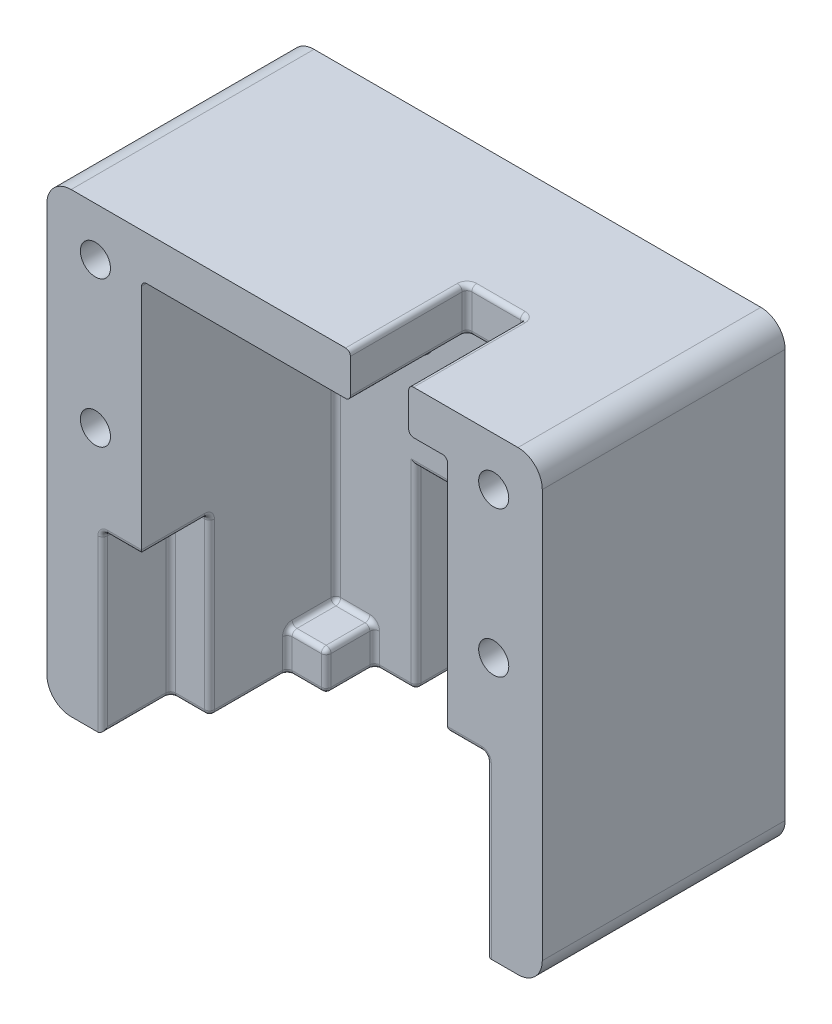
SolidWorks part; units mm, degrees
ref_plane "Front Plane" through (0, 0, 0) normal (0, 0, 1) x (1, 0, 0)
ref_plane "Top Plane" through (0, 0, 0) normal (0, 1, 0) x (1, 0, 0)
ref_plane "Right Plane" through (0, 0, 0) normal (1, 0, 0) x (0, 0, -1)
sketch "Sketch1" plane through (0, 0, 0) normal (0, 0, 1) x (1, 0, 0)
  line L0 (0, 0) -> (51, 0)
  line L1 (51, 0) -> (51, 47)
  line L2 (51, 47) -> (0, 47)
  line L3 (0, 47) -> (0, 0)
  dimension "D1" = 51
  dimension "D2" = 47
extrude "Boss-Extrude1" add sketch "Sketch1" along normal blind 5
sketch "Sketch2" plane through (0, 0, 5) normal (0, 0, 1) x (1, 0, 0)
  line L0 (0, 0) -> (0, 47)
  line L1 (0, 47) -> (51, 47)
  line L2 (51, 47) -> (51, 0)
  line L3 (51, 0) -> (41.25, 0)
  line L4 (0, 0) -> (51, 0) construction
  line L5 (41.25, 0) -> (41.25, 42.5)
  line L6 (41.25, 42.5) -> (9.75, 42.5)
  line L7 (9.75, 42.5) -> (9.75, 0)
  line L8 (9.75, 0) -> (0, 0)
  dimension "D1" = 9.75
  dimension "D2" = 9.75
  dimension "D3" = 4.5
extrude "Boss-Extrude2" add sketch "Sketch2" along normal blind 20
sketch "Sketch4" plane through (0, 0, 5) normal (0, 0, 1) x (1, 0, 0)
  line L0 (41.25, 0) -> (37.25, 0)
  line L1 (9.75, 0) -> (41.25, 0) construction
  line L2 (37.25, 0) -> (37.25, 4)
  line L3 (37.25, 4) -> (41.25, 4)
  line L4 (41.25, 42.5) -> (41.25, 0) construction
  line L5 (41.25, 4) -> (41.25, 0)
  line L6 (9.75, 0) -> (13.75, 0)
  line L7 (13.75, 0) -> (13.75, 4)
  line L8 (13.75, 4) -> (9.75, 4)
  line L9 (9.75, 0) -> (9.75, 42.5) construction
  line L10 (9.75, 4) -> (9.75, 0)
  dimension "D1" = 4
  dimension "D2" = 4
  dimension "D3" = 4
  dimension "D4" = 4
extrude "Boss-Extrude3" add sketch "Sketch4" along normal blind 5
sketch "Sketch5" plane through (0, 0, 25) normal (0, 0, 1) x (1, 0, 0)
  line L0 (41.25, 0) -> (41.25, 18)
  line L1 (41.25, 42.5) -> (41.25, 4) construction
  line L2 (41.25, 18) -> (45.25, 18)
  line L3 (45.25, 18) -> (45.25, 0)
  line L4 (41.25, 0) -> (51, 0) construction
  line L5 (45.25, 0) -> (41.25, 0)
  line L6 (9.75, 0) -> (9.75, 18)
  line L7 (9.75, 4) -> (9.75, 42.5) construction
  line L8 (9.75, 18) -> (5.75, 18)
  line L9 (5.75, 18) -> (5.75, 0)
  line L10 (0, 0) -> (9.75, 0) construction
  line L11 (5.75, 0) -> (9.75, 0)
  dimension "D1" = 4
  dimension "D2" = 18
  dimension "D3" = 18
  dimension "D4" = 4
extrude "Cut-Extrude1" cut sketch "Sketch5" against normal blind 7
sketch "Sketch7" plane through (0, 0, 25) normal (0, 0, 1) x (1, 0, 0)
  line L0 (37.25, 47) -> (37.25, 42.5)
  line L1 (51, 47) -> (0, 47) construction
  line L2 (9.75, 42.5) -> (41.25, 42.5) construction
  line L3 (37.25, 42.5) -> (31.25, 42.5)
  line L4 (9.75, 42.5) -> (41.25, 42.5) construction
  line L5 (31.25, 42.5) -> (31.25, 47)
  line L6 (31.25, 47) -> (37.25, 47)
  line L7 (41.25, 42.5) -> (41.25, 18) construction
  dimension "D1" = 4
  dimension "D2" = 6
extrude "Cut-Extrude2" cut sketch "Sketch7" against normal blind 12
sketch "Sketch8" plane through (0, 0, 5) normal (0, 0, 1) x (1, 0, 0)
  line L0 (25.5, 0) -> (33, 0)
  line L1 (13.75, 0) -> (37.25, 0) construction
  line L2 (33, 0) -> (33, 20)
  line L3 (33, 20) -> (18, 20)
  line L4 (18, 20) -> (18, 0)
  line L5 (18, 0) -> (25.5, 0)
  dimension "D1" = 7.5
  dimension "D2" = 7.5
  dimension "D3" = 20
extrude "Cut-Extrude3" cut sketch "Sketch8" against normal blind 4
sketch "Sketch9" plane through (0, 0, 25) normal (0, 0, 1) x (1, 0, 0)
  line L0 (0, 47) -> (0, 0) construction
  line L1 (31.25, 47) -> (0, 47) construction
  line L2 (51, 47) -> (37.25, 47) construction
  line L3 (51, 0) -> (51, 47) construction
  circle A0 centre (5, 27) radius 1.55
  circle A1 centre (5, 42) radius 1.55
  circle A2 centre (46, 42) radius 1.55
  circle A3 centre (46, 27) radius 1.55
  dimension "D1" = 3.1
  dimension "D2" = 3.1
  dimension "D3" = 3.1
  dimension "D4" = 3.1
  dimension "D5" = 15
  dimension "D6" = 15
  dimension "D7" = 5
  dimension "D8" = 5
  dimension "D9" = 5
  dimension "D10" = 5
extrude "Cut-Extrude4" cut sketch "Sketch9" against normal blind 10
sketch "Sketch10" plane through (0, 0, 5) normal (0, 0, 1) x (1, 0, 0)
  line L0 (9.75, 4) -> (9.75, 42.5) construction
  line L2 (41.25, 42.5) -> (41.25, 4) construction
  line L3 (9.75, 42.5) -> (41.25, 42.5) construction
  circle A0 centre (17.5, 32.5) radius 1.75
  circle A1 centre (33.5, 32.5) radius 1.75
  dimension "D1" = 3.5
  dimension "D2" = 3.5
  dimension "D3" = 7.75
  dimension "D4" = 7.75
  dimension "D5" = 10
extrude "Cut-Extrude5" cut sketch "Sketch10" against normal through all
sketch "Sketch11" plane through (0, 0, 5) normal (0, 0, 1) x (1, 0, 0)
  circle A0 centre (17.5, 32.5) radius 2.5
  circle A1 centre (33.5, 32.5) radius 2.5
  dimension "D1" = 5
  dimension "D2" = 5
extrude "Cut-Extrude6" cut sketch "Sketch11" against normal blind 2
fillet "Fillet1" radius 0.5 62 edges at (9.75, 4, 7.5) (9.75, 0, 14) (5.75, 0, 21.5) (18, 0, 3) (33, 0, 3) (41.25, 4, 7.5) (45.25, 0, 21.5) (37.25, 42.5, 19) (37.25, 47, 19) (31.25, 42.5, 19) (31.25, 47, 19) (9.75, 18, 21.5) (5.75, 18, 21.5) (7.75, 18, 25) (45.25, 18, 21.5) (41.25, 18, 21.5) (43.25, 18, 25) (13.75, 0, 7.5) (13.75, 4, 7.5) (11.75, 4, 10) (13.75, 2, 10) (11.75, 0, 10) (9.75, 2, 10) (5.75, 9, 18) (7.75, 18, 18) (9.75, 9, 18) (7.75, 0, 18) (15.875, 0, 5) (13.75, 2, 5) (11.75, 4, 5) (9.75, 23.25, 5) (25.5, 42.5, 5) (41.25, 23.25, 5) (39.25, 4, 5) (35.125, 0, 5) (33, 10, 5) (25.5, 20, 5) (18, 10, 5) (18, 10, 1) (25.5, 20, 1) (33, 10, 1) (25.5, 0, 1) (37.25, 4, 7.5) (37.25, 0, 7.5) (37.25, 2, 5) (39.25, 0, 10) (37.25, 2, 10) (39.25, 4, 10) (41.25, 2, 10) (41.25, 9, 18) (43.25, 18, 18) (45.25, 9, 18) (43.25, 0, 18) (37.25, 44.75, 13) (34.25, 42.5, 13) (31.25, 44.75, 13) (34.25, 47, 13) (41.25, 42.5, 15) (9.75, 42.5, 15) (41.25, 0, 14) (45.25, 9, 25) (5.75, 9, 25)
fillet "Fillet2" radius 2.5 4 edges at (0, 47, 12.5) (51, 47, 12.5) (51, 0, 12.5) (0, 0, 12.5)
